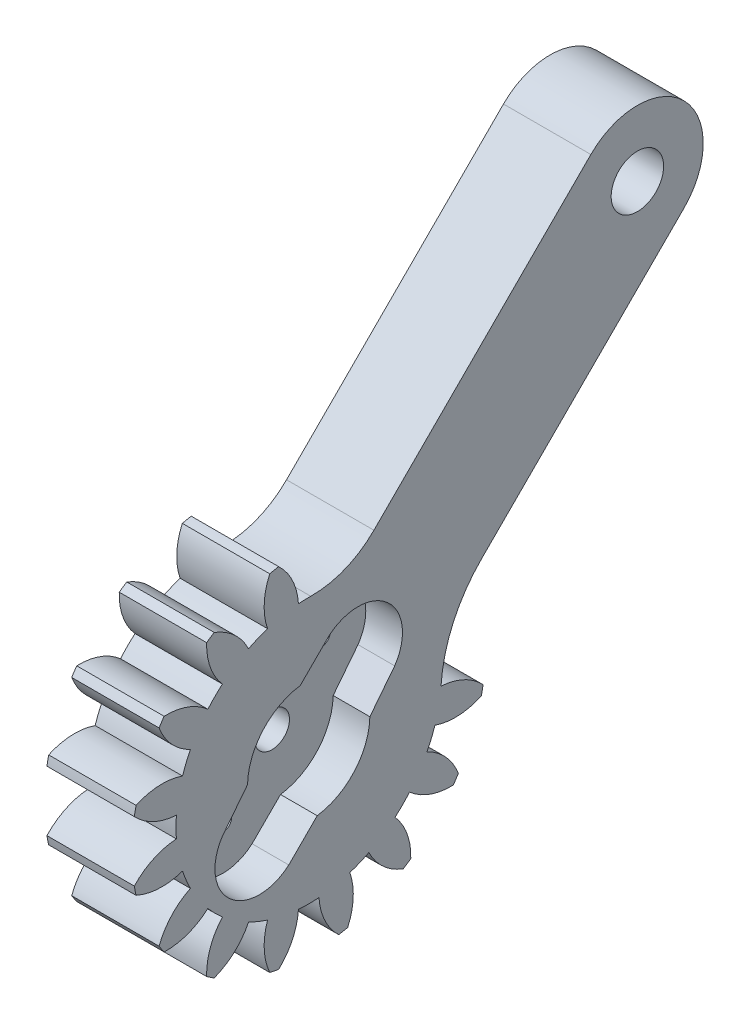
SolidWorks part; units mm, degrees
ref_plane "Plane1" through (0, 0, 0) normal (0, 0, 1) x (1, 0, 0)
ref_plane "Plane2" through (0, 0, 0) normal (0, 1, 0) x (1, 0, 0)
ref_plane "Plane3" through (0, 0, 0) normal (1, 0, 0) x (0, 0, -1)
other "Configuration Table"
sketch "HoldingSke" plane through (0, 0, 0) normal (0, 1, 0) x (1, 0, 0)
  line L0 (0, 0) -> (0.8695, -0.1848)
  line L1 (-15, 0) -> (100, 0) construction
  line L2 (0, 0) -> (-2.1039, 2.3779)
  line L3 (0, 0) -> (-11.863, 4.5341)
  line L4 (0, 0) -> (8.3015, 2.3804)
  line L5 (0, 0) -> (-46.8476, -17.4728)
  line L6 (0, 0) -> (-4.1448, -2.7965)
  line L7 (-2.1039, 2.3779) -> (8.6586, 51.2059)
  line L8 (-76.2, 54.61) -> (-75.3, 54.61)
  line L9 (-71.009, 38.7566) -> (-53.1078, 45.2721)
  line L10 (-76.2, 71.12) -> (104.1128, 71.12)
  line L11 (0, 0) -> (-5, 0)
  line L12 (-76.2, 101.6) -> (-76.158, 101.6)
  line L13 (24.9733, 27.94) -> (52.9518, 28.4284)
  line L14 (24.9733, 27.94) -> (24.9743, 27.94)
  line L15 (24.9733, 27.94) -> (100.4006, 29.5858)
  line L16 (-63.627, -1.125) -> (-12.827, -1.125)
  circle A0 centre (0, 0) radius 2.5
  circle A1 centre (0, 0) radius 7.5928
  circle A2 centre (0, 0) radius 37.5
  circle A3 centre (0, 0) radius 2.5
  dimension "MHD" = 15.1855
  dimension "Hub_dia" = 75
  dimension "Bore" = 5
  dimension "MBD" = 5
  dimension "Num_teeth" = 16
  dimension "Pitch" = 0.8889
  dimension "Overall_len" = 50
  dimension "Show_teeth" = 12
  dimension "Thickness" = 5
  dimension "OAL" = 50.0001
  dimension "T_dim" = 0.9
  dimension "Ap" = 20
  dimension "H" = 19.05
  dimension "Pitch_radius" = 180.3128
  dimension "Width" = 5
  dimension "Backlash" = 0.042
  dimension "Addendum_fac" = 1
  dimension "Dedendum_fac" = 1.25
  dimension "Clearance_fac" = 0.25
  dimension "Dedendum_add" = 0.001
  dimension "Module" = 1.125
sketch "BasProSke" plane through (0, 0, 0) normal (0, 1, 0) x (1, 0, 0)
  line L0 (-10, 0) -> (60, 0) construction
  line L1 (0, 0) -> (0, 10.125)
  line L2 (0, 0) -> (5, 0)
  line L3 (5, 0) -> (5, 10.125)
  line L4 (5, 10.125) -> (0, 10.125)
  dimension "Thickness" = 5
  dimension "Diameter" = 20.25
revolve "Base-Revolve" add sketch "BasProSke" angle 360 about L0
sketch "TooCutSke" plane through (0, 0, 0) normal (1, 0, 0) x (0, 0, -1)
  line L1 (0, 0) -> (0, 107) construction
  line L2 (0, 0) -> (-0.9556, 8.9491) construction
  line L3 (0, 0) -> (-3.4974, 17.5827) construction
  line L4 (-0.9556, 8.9491) -> (-1.7487, 8.7914) construction
  arc A0 (0.5882, 7.5699) -> (-0.5882, 7.5699) centre (0, 0) ccw
  arc A1 (1.7431, 9.9996) -> (-1.7431, 9.9996) centre (0, 0) ccw
  circle A2 centre (0, 0) radius 9 construction
  circle A3 centre (0, 0) radius 8.4572 construction
  arc A4 (-0.5882, 7.5699) -> (-1.7431, 9.9996) centre (-4.1815, 7.3512) ccw
  arc A5 (1.7431, 9.9996) -> (0.5882, 7.5699) centre (4.1815, 7.3512) ccw
  dimension "Root_dia" = 15.1855
  dimension "Overcut_dia" = 20.3008
  dimension "Pitch_dia" = 18
  dimension "Base_dia" = 16.9145
  dimension "Flank_rad" = 3.6
  dimension "Half_ang" = 11.25
  dimension "Half_CT" = 0.8087
extrude "ToothCut" cut sketch "TooCutSke" along normal through all
fillet "Breaks" [suppressed] radius 0.0225
fillet "RootFillets" [suppressed] radius 0.2823
pattern_circular "TeethCuts" count 13 every 22.5 about axis through (-10, 0, 0) along (1, 0, 0) of "ToothCut", "RootFillets", "Breaks"
sketch "HubNeaOneSke" plane through (0, 0, 0) normal (-1, 0, 0) x (0, 0, 1)
  circle A0 centre (0, 0) radius 7.5928
  dimension "Diameter" = 15.1855
extrude "HubNearOne" [suppressed] add sketch "HubNeaOneSke" along normal blind 45.0001
sketch "HubNeaBotSke" plane through (0, 0, 0) normal (-1, 0, 0) x (0, 0, 1)
  circle A0 centre (0, 0) radius 7.5928
  dimension "Diameter" = 15.1855
extrude "HubNearBoth" [suppressed] add sketch "HubNeaBotSke" along normal blind 22.5
ref_plane "FarPln" through (5, 0, 0) normal (1, 0, 0) x (0, 0, -1)
sketch "HubFarSke" plane through (5, 0, 0) normal (1, 0, 0) x (0, 0, -1)
  circle A0 centre (0, 0) radius 7.5928
  dimension "Diameter" = 15.1855
extrude "HubFar" [suppressed] add sketch "HubFarSke" along normal blind 22.5
sketch "BorSke" plane through (0, 0, 0) normal (1, 0, 0) x (0, 0, -1)
  circle A0 centre (0, 0) radius 2.5
  dimension "Diameter" = 5
extrude "Bore" cut sketch "BorSke" along normal mid plane 100.0001
sketch "KeySke" plane through (0, 0, 0) normal (1, 0, 0) x (0, 0, -1)
  line L0 (-1, 0) -> (-1, 3.4)
  line L1 (-1, 3.4) -> (1, 3.4)
  line L2 (1, 3.4) -> (1, 0)
  line L3 (0, 0) -> (0, 34) construction
  line L4 (-1, 0) -> (1, 0)
  dimension "Offset" = 3.4
  dimension "Width" = 2
extrude "Keyway" [suppressed] cut sketch "KeySke" along normal mid plane 100.0001
pattern_circular "Keyway2" [suppressed] count 2 every 90 about axis through (-10, 0, 0) along (1, 0, 0)
sketch "Esquisse1" plane through (5, 0, 0) normal (1, 0, 0) x (0, 0, -1)
  arc A0 (7.5699, 0.5882) -> (0.5882, 7.5699) centre (0, 0) ccw
  arc A1 (9.9779, 1.7197) -> (1.7197, 9.9779) centre (0, 0) ccw
  arc A2 (1.7197, 9.9779) -> (0.5882, 7.5699) centre (4.1815, 7.3512) ccw construction
  arc A3 (1.7197, 9.9779) -> (0.5882, 7.5699) centre (4.1815, 7.3512) ccw
  arc A4 (7.5699, 0.5882) -> (9.9779, 1.7197) centre (7.3512, 4.1815) ccw construction
  arc A5 (7.5699, 0.5882) -> (9.9779, 1.7197) centre (7.3512, 4.1815) ccw
extrude "Enlèv. mat.-Extru.1" cut sketch "Esquisse1" against normal blind 10
sketch "Esquisse2" plane through (5, 0, 0) normal (1, 0, 0) x (0, 0, -1)
  line L0 (0, 0) -> (17.3017, 17.3017) construction
  line L1 (0, 17.1027) -> (0, -13.4821) construction
  line L2 (2, 7.3246) -> (16.1421, 21.4667)
  line L3 (7.3246, 2) -> (21.4667, 16.1421)
  arc A1 (7.5699, -0.5882) -> (-0.5882, 7.5699) centre (0, 0) ccw construction
  arc A2 (16.1421, 21.4667) -> (21.4667, 16.1421) centre (18.8044, 18.8044) cw
  circle A3 centre (18.8044, 18.8044) radius 1.5
  arc A52 (9.9779, -1.7197) -> (7.5699, -0.5882) centre (7.3512, -4.1815) ccw
  arc A53 (7.5699, -0.5882) -> (-0.5882, 7.5699) centre (0, 0) ccw
  arc A54 (-0.5882, 7.5699) -> (-1.7197, 9.9779) centre (-4.1815, 7.3512) ccw
  arc A55 (-1.7197, 9.9779) -> (-2.2296, 9.8765) centre (0, 0) ccw
  arc A56 (-2.2296, 9.8765) -> (-2.3535, 7.2188) centre (1.05, 8.3918) ccw
  arc A57 (-2.3535, 7.2188) -> (-3.4403, 6.7686) centre (0, 0) ccw
  arc A58 (-3.4403, 6.7686) -> (-5.4072, 8.5603) centre (-6.6764, 5.1914) ccw
  arc A59 (-5.4072, 8.5603) -> (-5.8394, 8.2715) centre (0, 0) ccw
  arc A60 (-5.8394, 8.2715) -> (-4.9369, 5.7686) centre (-2.2413, 8.1548) ccw
  arc A61 (-4.9369, 5.7686) -> (-5.7686, 4.9369) centre (0, 0) ccw
  arc A62 (-5.7686, 4.9369) -> (-8.2715, 5.8394) centre (-8.1548, 2.2413) ccw
  arc A63 (-8.2715, 5.8394) -> (-8.5603, 5.4072) centre (0, 0) ccw
  arc A64 (-8.5603, 5.4072) -> (-6.7686, 3.4403) centre (-5.1914, 6.6764) ccw
  arc A65 (-6.7686, 3.4403) -> (-7.2188, 2.3535) centre (0, 0) ccw
  arc A66 (-7.2188, 2.3535) -> (-9.8765, 2.2296) centre (-8.3918, -1.05) ccw
  arc A67 (-9.8765, 2.2296) -> (-9.9779, 1.7197) centre (0, 0) ccw
  arc A68 (-9.9779, 1.7197) -> (-7.5699, 0.5882) centre (-7.3512, 4.1815) ccw
  arc A69 (-7.5699, 0.5882) -> (-7.5699, -0.5882) centre (0, 0) ccw
  arc A70 (-7.5699, -0.5882) -> (-9.9779, -1.7197) centre (-7.3512, -4.1815) ccw
  arc A71 (-9.9779, -1.7197) -> (-9.8765, -2.2296) centre (0, 0) ccw
  arc A72 (-9.8765, -2.2296) -> (-7.2188, -2.3535) centre (-8.3918, 1.05) ccw
  arc A73 (-7.2188, -2.3535) -> (-6.7686, -3.4403) centre (0, 0) ccw
  arc A74 (-6.7686, -3.4403) -> (-8.5603, -5.4072) centre (-5.1914, -6.6764) ccw
  arc A75 (-8.5603, -5.4072) -> (-8.2715, -5.8394) centre (0, 0) ccw
  arc A76 (-8.2715, -5.8394) -> (-5.7686, -4.9369) centre (-8.1548, -2.2413) ccw
  arc A77 (-5.7686, -4.9369) -> (-4.9369, -5.7686) centre (0, 0) ccw
  arc A78 (-4.9369, -5.7686) -> (-5.8394, -8.2715) centre (-2.2413, -8.1548) ccw
  arc A79 (-5.8394, -8.2715) -> (-5.4072, -8.5603) centre (0, 0) ccw
  arc A80 (-5.4072, -8.5603) -> (-3.4403, -6.7686) centre (-6.6764, -5.1914) ccw
  arc A81 (-3.4403, -6.7686) -> (-2.3535, -7.2188) centre (0, 0) ccw
  arc A82 (-2.3535, -7.2188) -> (-2.2296, -9.8765) centre (1.05, -8.3918) ccw
  arc A83 (-2.2296, -9.8765) -> (-1.7197, -9.9779) centre (0, 0) ccw
  arc A84 (-1.7197, -9.9779) -> (-0.5882, -7.5699) centre (-4.1815, -7.3512) ccw
  arc A85 (-0.5882, -7.5699) -> (0.5882, -7.5699) centre (0, 0) ccw
  arc A86 (0.5882, -7.5699) -> (1.7197, -9.9779) centre (4.1815, -7.3512) ccw
  arc A87 (1.7197, -9.9779) -> (2.2296, -9.8765) centre (0, 0) ccw
  arc A88 (2.2296, -9.8765) -> (2.3535, -7.2188) centre (-1.05, -8.3918) ccw
  arc A89 (2.3535, -7.2188) -> (3.4403, -6.7686) centre (0, 0) ccw
  arc A90 (3.4403, -6.7686) -> (5.4072, -8.5603) centre (6.6764, -5.1914) ccw
  arc A91 (5.4072, -8.5603) -> (5.8394, -8.2715) centre (0, 0) ccw
  arc A92 (5.8394, -8.2715) -> (4.9369, -5.7686) centre (2.2413, -8.1548) ccw
  arc A93 (4.9369, -5.7686) -> (5.7686, -4.9369) centre (0, 0) ccw
  arc A94 (5.7686, -4.9369) -> (8.2715, -5.8394) centre (8.1548, -2.2413) ccw
  arc A95 (8.2715, -5.8394) -> (8.5603, -5.4072) centre (0, 0) ccw
  arc A96 (8.5603, -5.4072) -> (6.7686, -3.4403) centre (5.1914, -6.6764) ccw
  arc A97 (6.7686, -3.4403) -> (7.2188, -2.3535) centre (0, 0) ccw
  arc A98 (7.2188, -2.3535) -> (9.8765, -2.2296) centre (8.3918, 1.05) ccw
  arc A99 (9.8765, -2.2296) -> (9.9779, -1.7197) centre (0, 0) ccw
  arc A100 (9.9779, -1.7197) -> (7.5699, -0.5882) centre (7.3512, -4.1815) ccw
  arc A101 (7.5699, -0.5882) -> (-0.5882, 7.5699) centre (0, 0) ccw
  arc A102 (-0.5882, 7.5699) -> (-1.7197, 9.9779) centre (-4.1815, 7.3512) ccw
  arc A103 (-1.7197, 9.9779) -> (-2.2296, 9.8765) centre (0, 0) ccw
  arc A104 (-2.2296, 9.8765) -> (-2.3535, 7.2188) centre (1.05, 8.3918) ccw
  arc A105 (-2.3535, 7.2188) -> (-3.4403, 6.7686) centre (0, 0) ccw
  arc A106 (-3.4403, 6.7686) -> (-5.4072, 8.5603) centre (-6.6764, 5.1914) ccw
  arc A107 (-5.4072, 8.5603) -> (-5.8394, 8.2715) centre (0, 0) ccw
  arc A108 (-5.8394, 8.2715) -> (-4.9369, 5.7686) centre (-2.2413, 8.1548) ccw
  arc A109 (-4.9369, 5.7686) -> (-5.7686, 4.9369) centre (0, 0) ccw
  arc A110 (-5.7686, 4.9369) -> (-8.2715, 5.8394) centre (-8.1548, 2.2413) ccw
  arc A111 (-8.2715, 5.8394) -> (-8.5603, 5.4072) centre (0, 0) ccw
  arc A112 (-8.5603, 5.4072) -> (-6.7686, 3.4403) centre (-5.1914, 6.6764) ccw
  arc A113 (-6.7686, 3.4403) -> (-7.2188, 2.3535) centre (0, 0) ccw
  arc A114 (-7.2188, 2.3535) -> (-9.8765, 2.2296) centre (-8.3918, -1.05) ccw
  arc A115 (-9.8765, 2.2296) -> (-9.9779, 1.7197) centre (0, 0) ccw
  arc A116 (-9.9779, 1.7197) -> (-7.5699, 0.5882) centre (-7.3512, 4.1815) ccw
  arc A117 (-7.5699, 0.5882) -> (-7.5699, -0.5882) centre (0, 0) ccw
  arc A118 (-7.5699, -0.5882) -> (-9.9779, -1.7197) centre (-7.3512, -4.1815) ccw
  arc A119 (-9.9779, -1.7197) -> (-9.8765, -2.2296) centre (0, 0) ccw
  arc A120 (-9.8765, -2.2296) -> (-7.2188, -2.3535) centre (-8.3918, 1.05) ccw
  arc A121 (-7.2188, -2.3535) -> (-6.7686, -3.4403) centre (0, 0) ccw
  arc A122 (-6.7686, -3.4403) -> (-8.5603, -5.4072) centre (-5.1914, -6.6764) ccw
  arc A123 (-8.5603, -5.4072) -> (-8.2715, -5.8394) centre (0, 0) ccw
  arc A124 (-8.2715, -5.8394) -> (-5.7686, -4.9369) centre (-8.1548, -2.2413) ccw
  arc A125 (-5.7686, -4.9369) -> (-4.9369, -5.7686) centre (0, 0) ccw
  arc A126 (-4.9369, -5.7686) -> (-5.8394, -8.2715) centre (-2.2413, -8.1548) ccw
  arc A127 (-5.8394, -8.2715) -> (-5.4072, -8.5603) centre (0, 0) ccw
  arc A128 (-5.4072, -8.5603) -> (-3.4403, -6.7686) centre (-6.6764, -5.1914) ccw
  arc A129 (-3.4403, -6.7686) -> (-2.3535, -7.2188) centre (0, 0) ccw
  arc A130 (-2.3535, -7.2188) -> (-2.2296, -9.8765) centre (1.05, -8.3918) ccw
  arc A131 (-2.2296, -9.8765) -> (-1.7197, -9.9779) centre (0, 0) ccw
  arc A132 (-1.7197, -9.9779) -> (-0.5882, -7.5699) centre (-4.1815, -7.3512) ccw
  arc A133 (-0.5882, -7.5699) -> (0.5882, -7.5699) centre (0, 0) ccw
  arc A134 (0.5882, -7.5699) -> (1.7197, -9.9779) centre (4.1815, -7.3512) ccw
  arc A135 (1.7197, -9.9779) -> (2.2296, -9.8765) centre (0, 0) ccw
  arc A136 (2.2296, -9.8765) -> (2.3535, -7.2188) centre (-1.05, -8.3918) ccw
  arc A137 (2.3535, -7.2188) -> (3.4403, -6.7686) centre (0, 0) ccw
  arc A138 (3.4403, -6.7686) -> (5.4072, -8.5603) centre (6.6764, -5.1914) ccw
  arc A139 (5.4072, -8.5603) -> (5.8394, -8.2715) centre (0, 0) ccw
  arc A140 (5.8394, -8.2715) -> (4.9369, -5.7686) centre (2.2413, -8.1548) ccw
  arc A141 (4.9369, -5.7686) -> (5.7686, -4.9369) centre (0, 0) ccw
  arc A142 (5.7686, -4.9369) -> (8.2715, -5.8394) centre (8.1548, -2.2413) ccw
  arc A143 (8.2715, -5.8394) -> (8.5603, -5.4072) centre (0, 0) ccw
  arc A144 (8.5603, -5.4072) -> (6.7686, -3.4403) centre (5.1914, -6.6764) ccw
  arc A145 (6.7686, -3.4403) -> (7.2188, -2.3535) centre (0, 0) ccw
  arc A146 (7.2188, -2.3535) -> (9.8765, -2.2296) centre (8.3918, 1.05) ccw
  arc A147 (9.8765, -2.2296) -> (9.9779, -1.7197) centre (0, 0) ccw
  arc M8 (7.5699, -0.5882) -> (-0.5882, 7.5699) centre (0, 0) ccw
  dimension "D4" = 3
  dimension "D1" = 45
  dimension "D2" = 20
  dimension "D3" = 2
  dimension "D5" = 0
extrude "Boss.-Extru.1" add sketch "Esquisse2" against normal through all contours A2 L2 L3 A3 M8
sketch "Esquisse3" plane through (5, 0, 0) normal (1, 0, 0) x (0, 0, -1)
  circle A0 centre (0, 0) radius 2.5 construction
  circle A1 centre (0, 0) radius 2.5
extrude "Boss.-Extru.2" add sketch "Esquisse3" against normal through all from offset 1 offset against normal yes
sketch "Esquisse4" plane through (4, 0, 0) normal (1, 0, 0) x (0, 0, -1)
  circle A0 centre (0, 0) radius 1
extrude "Enlèv. mat.-Extru.2" cut sketch "Esquisse4" against normal blind 10
fillet "Congé1" radius 5 1 edges at (2.5, 7.3246, -2)
fillet "Congé2" radius 8 1 edges at (2.5, 2, -7.3246)
sketch "Esquisse6" plane through (5, 0, 0) normal (1, 0, 0) x (0, 0, -1)
  line L4 (4.8791, 1.772) -> (3.4496, -0.0501)
  line L5 (-0.4633, 3.4188) -> (1.1743, 5.0564)
  line L7 (-1.1743, -5.0563) -> (0.4633, -3.4188)
  line L8 (-0.4867, 3.466) -> (1.1401, 5.0929)
  line L9 (4.9194, 1.7424) -> (3.4993, -0.0677)
  line L10 (-1.1401, -5.0928) -> (0.4867, -3.466)
  line L11 (-4.9195, -1.7425) -> (-3.4993, 0.0677)
  line L12 (-4.8791, -1.772) -> (-3.4496, 0.0501) construction
  arc A6 (0.4633, -3.4188) -> (3.4496, -0.0501) centre (0, 0) ccw
  arc A7 (4.8791, 1.772) -> (1.1743, 5.0564) centre (2.8193, 3.1802) ccw
  arc A9 (-1.1743, -5.0563) -> (-4.8791, -1.772) centre (-2.8193, -3.1802) cw
  arc A10 (4.9194, 1.7424) -> (1.1401, 5.0929) centre (2.8193, 3.1802) ccw
  arc A11 (0.4867, -3.466) -> (3.4993, -0.0677) centre (0, 0) ccw
  arc A12 (-1.1401, -5.0928) -> (-4.9195, -1.7425) centre (-2.8193, -3.1802) cw
  arc A13 (-0.4867, 3.466) -> (-3.4993, 0.0677) centre (0, 0) ccw
  arc A14 (-0.4633, 3.4188) -> (-3.4496, 0.0501) centre (0, 0) ccw construction
  dimension "D1" = 0.05
extrude "Enlèv. mat.-Extru.4" cut sketch "Esquisse6" against normal blind 2.1
sketch "Esquisse8" plane through (2.9, 0, 0) normal (1, 0, 0) x (0, 0, -1)
  circle A0 centre (-2.8193, -3.1802) radius 0.515
  circle A1 centre (2.8193, 3.1802) radius 0.515
extrude "Enlèv. mat.-Extru.5" cut sketch "Esquisse8" against normal through all
equation "' \"Module@HoldingSke\" = 6.35"
equation "' \"Num_teeth@HoldingSke\" = 12"
equation "' \"Ap@HoldingSke\" =  20"
equation "' \"Ap@HoldingSke\" = 20"
equation "' \"Width@HoldingSke\" = 0.5 * 25.4"
equation "' \"Hub_dia@HoldingSke\"= 1 * 25.4"
equation "' \"Hub_dia@HoldingSke\" = 1 * 25.4"
equation "' \"Overall_len@HoldingSke\" = 1.0 * 25.4"
equation "' \"Bore@HoldingSke\" = 0.75 * 25.4"
equation "' \"T_dim@HoldingSke\" = 0.1 * 25.4"
equation "' \"Width@KeySke\" = 0.25 * 25.4"
equation "' \"Show_teeth@HoldingSke\" = 13"
equation "' \"Backlash@HoldingSke\" = 0.009 * 25.4"
equation "' \"Addendum_fac@HoldingSke\" = 1.0"
equation "' \"Dedendum_fac@HoldingSke\" = 1.25"
equation "' \"Dedendum_add@HoldingSke\" = 0.00005 * 25.4"
equation "' \"Clearance_fac@HoldingSke\" = 0.25"
equation "\"Pitch@HoldingSke\" = 1 / \"Module@HoldingSke\""
equation "\"Overcut_dia@TooCutSke\" = (\"Num_teeth@HoldingSke\" + 2 * \"Addendum_fac@HoldingSke\") / \"Pitch@HoldingSke\" + 0.002 * 25.4"
equation "\"Pitch_dia@TooCutSke\" = \"Num_teeth@HoldingSke\" / \"Pitch@HoldingSke\""
equation "\"Base_dia@TooCutSke\" = \"Num_teeth@HoldingSke\" / \"Pitch@HoldingSke\" * cos((\"Ap@HoldingSke\"  * 3.14159265 / 180))"
equation "\"Root_dia@TooCutSke\" = (\"Num_teeth@HoldingSke\" + 2) / \"Pitch@HoldingSke\" - 2 * (\"Addendum_fac@HoldingSke\" + \"Dedendum_fac@HoldingSke\") / \"Pitch@HoldingSke\" - \"Dedendum_add@HoldingSke\" * 2"
equation "\"Half_ang@TooCutSke\" = 180 / \"Num_teeth@HoldingSke\""
equation "\"Half_CT@TooCutSke\" = \"Num_teeth@HoldingSke\" / \"Pitch@HoldingSke\" * sin((3.14159265 / 2 / \"Num_teeth@HoldingSke\")) / 2 - 7 * \"Backlash@HoldingSke\" / 4"
equation "\"Flank_rad@TooCutSke\" = \"Num_teeth@HoldingSke\" / \"Pitch@HoldingSke\" / 5"
equation "\"Radius@RootFillets\" = \"Clearance_fac@HoldingSke\" / \"Pitch@HoldingSke\" + \"Dedendum_add@HoldingSke\""
equation "\"Break_rad@Breaks\" = 0.02 / \"Pitch@HoldingSke\""
equation "\"Thickness@HoldingSke\" = \"Width@HoldingSke\""
equation "\"OAL@HoldingSke\" = \"Thickness@HoldingSke\""
equation "\"MHD@HoldingSke\" = (\"Num_teeth@HoldingSke\" + 2) / \"Pitch@HoldingSke\" - 2 * (\"Addendum_fac@HoldingSke\" + \"Dedendum_fac@HoldingSke\")  / \"Pitch@HoldingSke\" - \"Dedendum_add@HoldingSke\" * 2"
equation "\"MBD@HoldingSke\" = (\"Num_teeth@HoldingSke\" + 2) / \"Pitch@HoldingSke\" - 2 * (\"Addendum_fac@HoldingSke\" + \"Dedendum_fac@HoldingSke\")  / \"Pitch@HoldingSke\" - \"Dedendum_add@HoldingSke\" * 2 - 0.002 * 25.4"
equation "\"MHD@HoldingSke\" = ((sgn( \"MHD@HoldingSke\" - \"Hub_dia@HoldingSke\" )-1)*( \"MHD@HoldingSke\" - \"Hub_dia@HoldingSke\" ))/-2+ \"Hub_dia@HoldingSke\""
equation "\"MBD@HoldingSke\" = ((sgn( \"MBD@HoldingSke\" - \"Bore@HoldingSke\" )-1)*( \"MBD@HoldingSke\" - \"Bore@HoldingSke\" ))/-2+ \"Bore@HoldingSke\""
equation "\"OAL@HoldingSke\" = ((sgn( \"OAL@HoldingSke\" - \"Overall_len@HoldingSke\" )+1)*( \"OAL@HoldingSke\" - \"Overall_len@HoldingSke\" ))/2 + \"Overall_len@HoldingSke\" + 0.000002 * 25.4"
equation "\"Num_teeth@TeethCuts\" = int( \"Show_teeth@HoldingSke\" ) + 1"
equation "\"Num_teeth@TeethCuts\" = ((sgn( \"Num_teeth@TeethCuts\" - \"Num_teeth@HoldingSke\" )-1)*( \"Num_teeth@TeethCuts\" - \"Num_teeth@HoldingSke\" ))/-2+ \"Num_teeth@HoldingSke\""
equation "\"Num_teeth@TeethCuts\" = ((sgn( \"Num_teeth@TeethCuts\" - 2.0)+1)*( \"Num_teeth@TeethCuts\" - 2.0))/2 +2.0"
equation "\"Angle@TeethCuts\" = 360.0 / \"Num_teeth@HoldingSke\""
equation "\"Diameter@BasProSke\" = (\"Num_teeth@HoldingSke\" + 2 * \"Addendum_fac@HoldingSke\") / \"Pitch@HoldingSke\""
equation "\"Thickness@BasProSke\"  = \"Thickness@HoldingSke\""
equation "' \"Fillet_rad@BasProSke\" =  \"Thickness@HoldingSke\" * 0.05"
equation "' \"Fillet_rad@BasProSke\" = \"Thickness@HoldingSke\" * 0.05"
equation "\"MHD@HoldingSke\" = ((sgn( \"MHD@HoldingSke\" - \"Root_dia@TooCutSke\" )-1)*( \"MHD@HoldingSke\" - \"Root_dia@TooCutSke\" ))/-2+ \"Root_dia@TooCutSke\""
equation "\"Diameter@HubNeaOneSke\" = \"MHD@HoldingSke\""
equation "\"Length@HubNearOne\" = \"OAL@HoldingSke\" - \"Thickness@BasProSke\""
equation "\"Diameter@HubNeaBotSke\" = \"MHD@HoldingSke\""
equation "\"Length@HubNearBoth\" = ( \"OAL@HoldingSke\" - \"Thickness@BasProSke\" ) / 2.0"
equation "\"Thickness@FarPln\" = \"Thickness@BasProSke\""
equation "\"Diameter@HubFarSke\" = \"MHD@HoldingSke\""
equation "\"Length@HubFar\" = ( \"OAL@HoldingSke\" - \"Thickness@BasProSke\" ) / 2.0"
equation "\"Diameter@BorSke\" = \"MBD@HoldingSke\""
equation "\"D1@Bore\" = \"OAL@HoldingSke\" * 2.0"
equation "\"D1@Keyway\" = \"OAL@HoldingSke\" * 2.0"
equation "\"Offset@KeySke\" = \"T_dim@HoldingSke\" + \"MBD@HoldingSke\" / 2.0"
